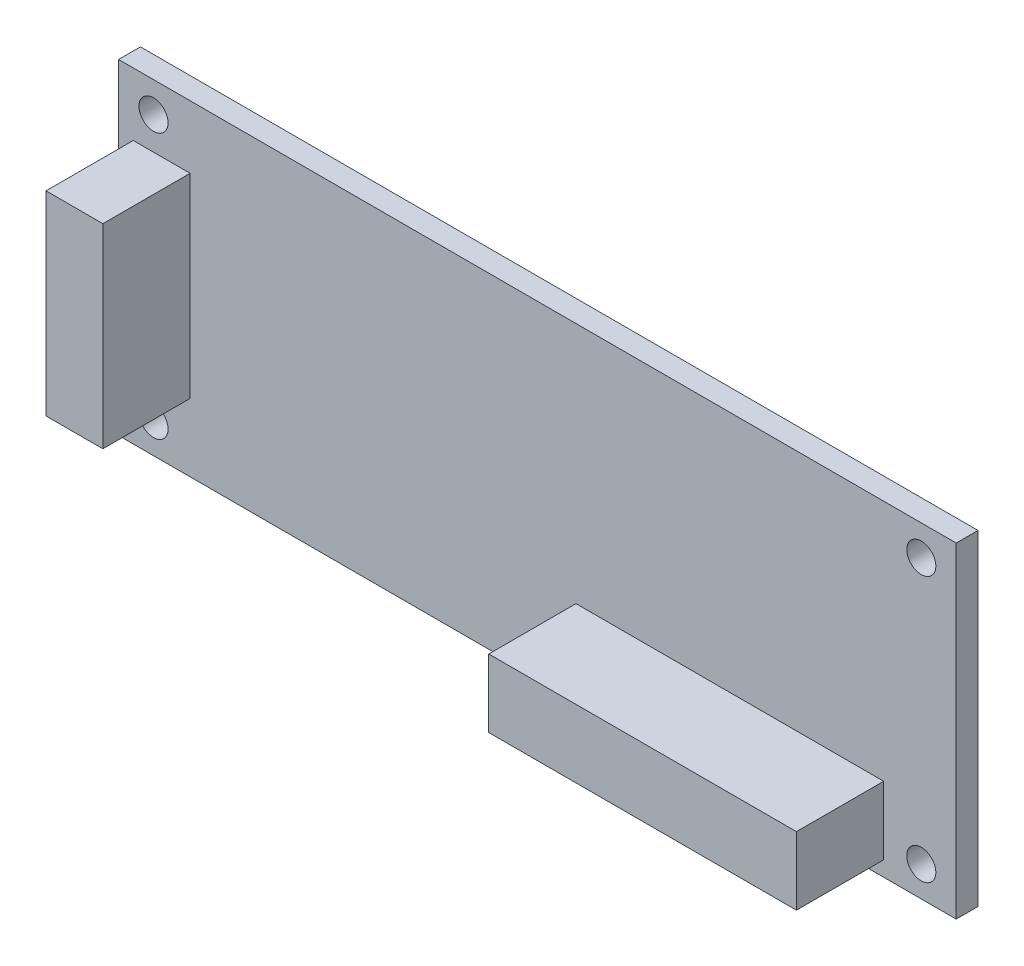
SolidWorks part; units mm, degrees
ref_plane "Front Plane" through (0, 0, 0) normal (0, 0, 1) x (1, 0, 0)
ref_plane "Top Plane" through (0, 0, 0) normal (0, 1, 0) x (1, 0, 0)
ref_plane "Right Plane" through (0, 0, 0) normal (1, 0, 0) x (0, 0, -1)
sketch "Sketch1" plane through (0, 0, 0) normal (0, 0, 1) x (1, 0, 0)
  line L1 (-45.72, -17.78) -> (45.72, -17.78)
  line L2 (-45.72, -17.78) -> (-45.72, 17.78)
  line L3 (-45.72, 17.78) -> (45.72, 17.78)
  line L4 (45.72, -17.78) -> (45.72, 17.78)
  line L5 (-45.72, -17.78) -> (45.72, 17.78) construction
  line L6 (-45.72, 17.78) -> (45.72, -17.78) construction
  point P0 (0, 0)
  dimension "D1" = 91.44
  dimension "D2" = 35.56
extrude "Boss-Extrude1" add sketch "Sketch1" along normal blind 2.3813
sketch "Sketch2" plane through (0, 0, 2.3813) normal (0, 0, 1) x (1, 0, 0)
  line L0 (-45.72, 17.78) -> (-45.72, -17.78) construction
  line L1 (45.72, 17.78) -> (-45.72, 17.78) construction
  circle A0 centre (-41.91, 14.478) radius 1.5875
  dimension "D1" = 3.175
  dimension "D2" = 3.81
  dimension "D3" = 3.302
extrude "Cut-Extrude1" cut sketch "Sketch2" against normal through all
mirror "Mirror1" about plane through (0, 0, 0) normal (1, 0, 0) of "Cut-Extrude1"
mirror "Mirror2" about plane through (0, 0, 0) normal (0, 1, 0) of "Mirror1", "Cut-Extrude1"
sketch "Sketch3" plane through (0, 0, 2.3813) normal (0, 0, 1) x (1, 0, 0)
  line L1 (-44.1229, 10.9199) -> (-37.9147, 10.9199)
  line L2 (-44.1229, 10.9199) -> (-44.1229, -10.3656)
  line L3 (-44.1229, -10.3656) -> (-37.9147, -10.3656)
  line L4 (-37.9147, 10.9199) -> (-37.9147, -10.3656)
  line L5 (37.8038, -16.1304) -> (4.2127, -16.1304)
  line L6 (37.8038, -16.1304) -> (37.8038, -8.7026)
  line L7 (37.8038, -8.7026) -> (4.2127, -8.7026)
  line L8 (4.2127, -16.1304) -> (4.2127, -8.7026)
extrude "Boss-Extrude2" add sketch "Sketch3" along normal blind 9.525
